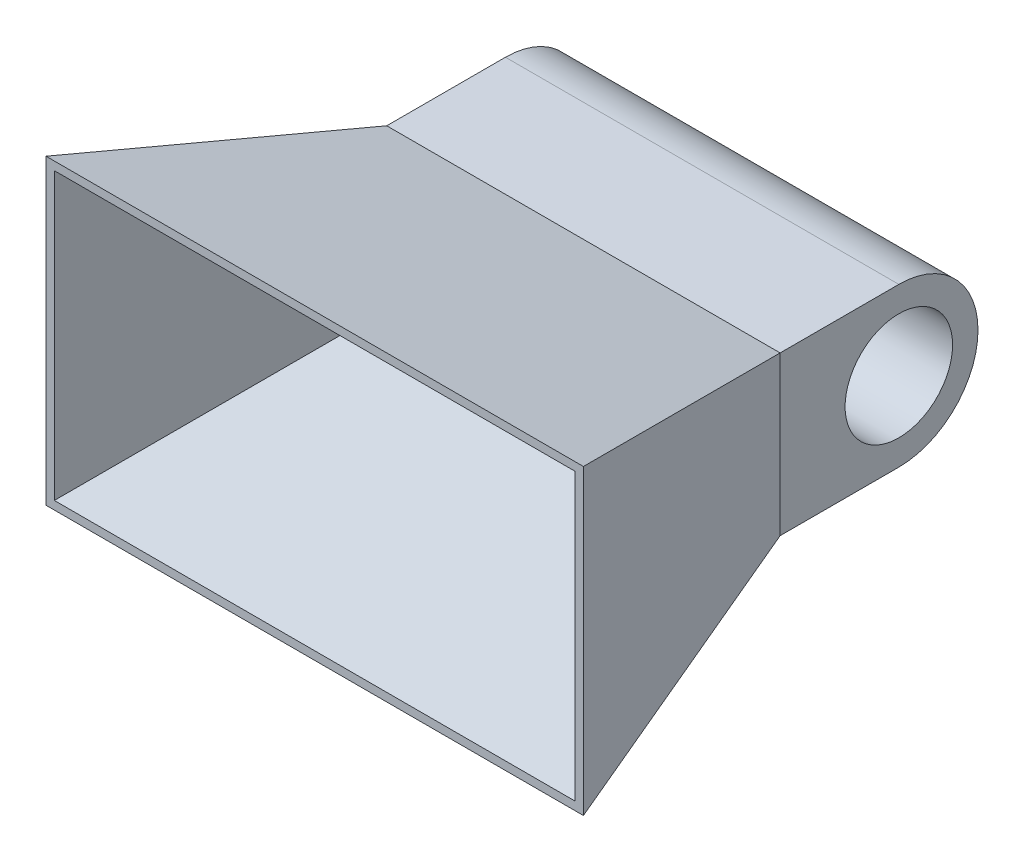
SolidWorks part; units mm, degrees
ref_plane "Front Plane" through (0, 0, 0) normal (0, 0, 1) x (1, 0, 0)
ref_plane "Top Plane" through (0, 0, 0) normal (0, 1, 0) x (1, 0, 0)
ref_plane "Right Plane" through (0, 0, 0) normal (1, 0, 0) x (0, 0, -1)
sketch "Camera Cone Sketch" plane through (0, 0, 0) normal (0, 0, 1) x (1, 0, 0)
  line L1 (-100, 56.25) -> (100, 56.25)
  line L2 (-100, 56.25) -> (-100, -56.25)
  line L3 (-100, -56.25) -> (100, -56.25)
  line L4 (100, 56.25) -> (100, -56.25)
  line L5 (-100, 56.25) -> (100, -56.25) construction
  line L6 (-100, -56.25) -> (100, 56.25) construction
  point P0 (0, 0)
extrude "Camera Cone Extrude" add sketch "Camera Cone Sketch" against normal blind 100 draft 15
shell "Camera Cone Shell" thickness 3
ref_plane "Lefthand Plane" through (73.2051, 0, 0) normal (1, 0, 0) x (0, 0, -1)
ref_plane "Righthand Plane" through (-73.2051, 0, 0) normal (-1, 0, 0) x (0, 0, 1)
sketch "Hinge Sketch" plane through (73.2051, 0, 0) normal (1, 0, 0) x (0, 0, -1)
  line L0 (144.1826, 29.4551) -> (144.1826, -29.4551) construction
  line L1 (100, 29.4551) -> (144.1826, 29.4551)
  line L2 (100, 29.4551) -> (100, -29.4551)
  line L3 (100, -29.4551) -> (144.1826, -29.4551)
  line L4 (144.1826, 29.4551) -> (144.1826, -29.4551) construction
  line L5 (114.7275, 0) -> (114.7275, 29.4551) construction
  line L6 (114.7275, 14.7275) -> (144.1826, 14.7275) construction
  line L7 (100, -29.4551) -> (100, 29.4551) construction
  line L8 (114.7275, 0) -> (114.7275, -29.4551) construction
  line L9 (129.4551, 29.4551) -> (129.4551, -29.4551) construction
  line L10 (114.7275, 0) -> (100, 0) construction
  line L11 (129.4551, 0) -> (144.1826, 0) construction
  line L12 (129.4551, 0) -> (114.7275, 0) construction
  line L13 (144.1826, 29.4551) -> (100, -29.4551) construction
  line L14 (144.1826, 0) -> (173.6377, 0) construction
  arc A0 (144.1826, -29.4551) -> (144.1826, 29.4551) centre (144.1826, 0) ccw
extrude "Hinge Extrude" add sketch "Hinge Sketch" against normal up to surface (146.4102 mm away) up to plane "Righthand Plane"
sketch "Hinge Hole Sketch" plane through (73.2051, 0, 0) normal (1, 0, 0) x (0, 0, -1)
  circle A0 centre (144.1826, 0) radius 20
  arc A1 (144.1826, -29.4551) -> (144.1826, 29.4551) centre (144.1826, 0) ccw construction
  dimension "D2" = 40
extrude "Hinge Hole Cut" cut sketch "Hinge Hole Sketch" against normal up to surface (146.4102 mm away) up to face at (-73.2051, 0, -129.4551)
equation "\"Camera Width\"= 200mm"
equation "\"Camera Height\"= \"Camera Width\" * ( 9 / 16 )"
